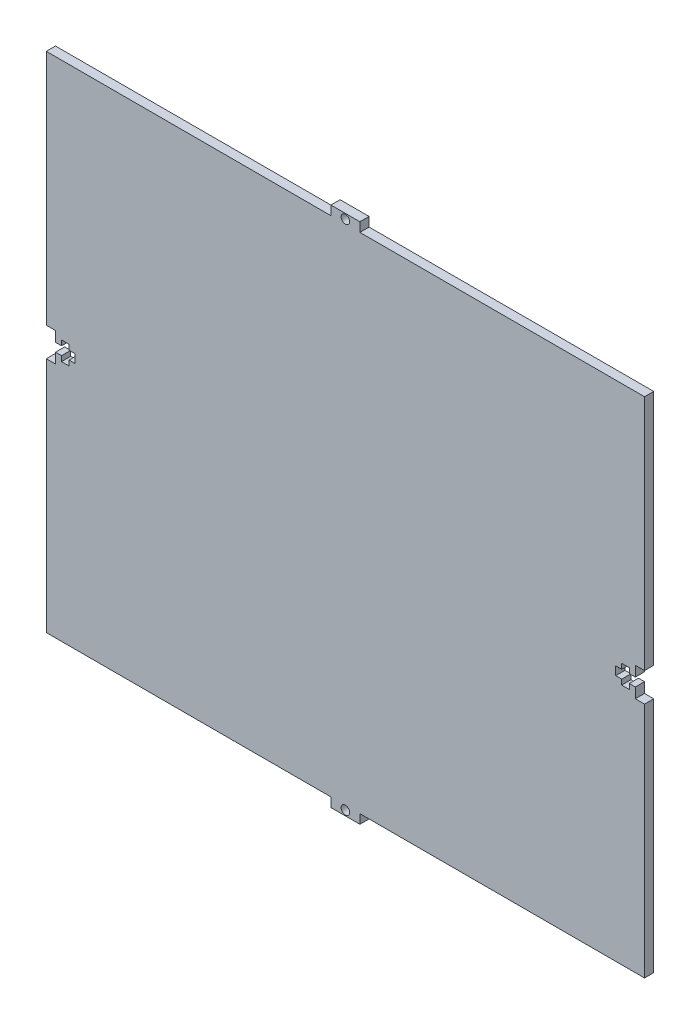
SolidWorks part; units mm, degrees
ref_plane "Front Plane" through (0, 0, 0) normal (0, 0, 1) x (1, 0, 0)
ref_plane "Top Plane" through (0, 0, 0) normal (0, 1, 0) x (1, 0, 0)
ref_plane "Right Plane" through (0, 0, 0) normal (1, 0, 0) x (0, 0, -1)
sketch "Sketch2" plane through (0, 0, 0) normal (0, 0, 1) x (1, 0, 0)
  line L1 (-103.18, -86.82) -> (103.18, -86.82)
  line L2 (-103.18, -86.82) -> (-103.18, 86.82)
  line L3 (-103.18, 86.82) -> (103.18, 86.82)
  line L4 (103.18, -86.82) -> (103.18, 86.82)
  line L5 (-103.18, -86.82) -> (103.18, 86.82) construction
  line L6 (-103.18, 86.82) -> (103.18, -86.82) construction
  point P0 (0, 0)
  dimension "D1" = 173.64
  dimension "D2" = 206.36
extrude "Boss-Extrude1" add sketch "Sketch2" along normal blind 3.18
sketch "Sketch3" plane through (0, 0, 3.18) normal (0, 0, 1) x (1, 0, 0)
  line L0 (103.18, 86.82) -> (-103.18, 86.82) construction
  line L5 (0, 86.82) -> (0, 25.4128) construction
  line L19 (-103.18, 0) -> (103.18, 0) construction
  line L20 (-103.18, 86.82) -> (-103.18, -86.82) construction
  line L21 (103.18, -86.82) -> (103.18, 86.82) construction
  line L38 (-95.32, -1.47) -> (-95.32, -3.25)
  line L39 (-103.18, 5) -> (-100, 5)
  line L40 (-103.18, 5) -> (-103.18, -5)
  line L41 (-103.18, -5) -> (-100, -5)
  line L42 (-100, 5) -> (-100, 1.47)
  line L43 (-100, -1.47) -> (-97.92, -1.47)
  line L45 (-100, 1.47) -> (-97.92, 1.47)
  line L46 (-93.25, -1.47) -> (-93.25, 1.47)
  line L47 (-97.92, 3.25) -> (-95.32, 3.25)
  line L48 (-97.92, 3.25) -> (-97.92, 1.47)
  line L49 (-97.92, -3.25) -> (-95.32, -3.25)
  line L50 (-95.32, 3.25) -> (-95.32, 1.47)
  line L51 (-95.32, -1.47) -> (-93.25, -1.47)
  line L52 (-97.92, -1.47) -> (-97.92, -3.25)
  line L53 (-100, -1.47) -> (-100, -5)
  line L54 (-95.32, 1.47) -> (-93.25, 1.47)
  point P55 (-96.62, 3.25)
  dimension "D8" = 10
  dimension "D9" = 2.6
  dimension "D10" = 6.5
  dimension "D11" = 3.18
  dimension "D12" = 2.94
  dimension "D13" = 2.08
  dimension "D14" = 6.75
extrude "Cut-Extrude1" cut sketch "Sketch3" against normal through all
sketch "Sketch9" plane through (0, 86.82, 0) normal (0, 1, 0) x (1, 0, 0)
  line L0 (0, 0) -> (0, -11.7583) construction
  line L1 (103.18, 0) -> (-103.18, 0) construction
  line L2 (-5, 0) -> (5, 0)
  line L3 (-5, 0) -> (-5, -3.18)
  line L4 (-5, -3.18) -> (5, -3.18)
  line L5 (5, 0) -> (5, -3.18)
  line L6 (103.18, -3.18) -> (-103.18, -3.18) construction
  dimension "D1" = 10
extrude "Boss-Extrude4" add sketch "Sketch9" along normal blind 3.18
sketch "Sketch11" plane through (0, 0, 3.18) normal (0, 0, 1) x (1, 0, 0)
  line L0 (0, 0) -> (0, 84.6375) construction
  line L1 (-5, 90) -> (5, 90) construction
  circle A0 centre (0, 88.25) radius 1.47
  dimension "D1" = 2.94
  dimension "D2" = 1.75
extrude "Cut-Extrude3" cut sketch "Sketch11" against normal through all
mirror "Mirror1" about plane through (0, 0, 0) normal (1, 0, 0) of "Cut-Extrude1"
mirror "Mirror2" about plane through (0, 0, 0) normal (0, 1, 0) of "Cut-Extrude3", "Boss-Extrude4"
